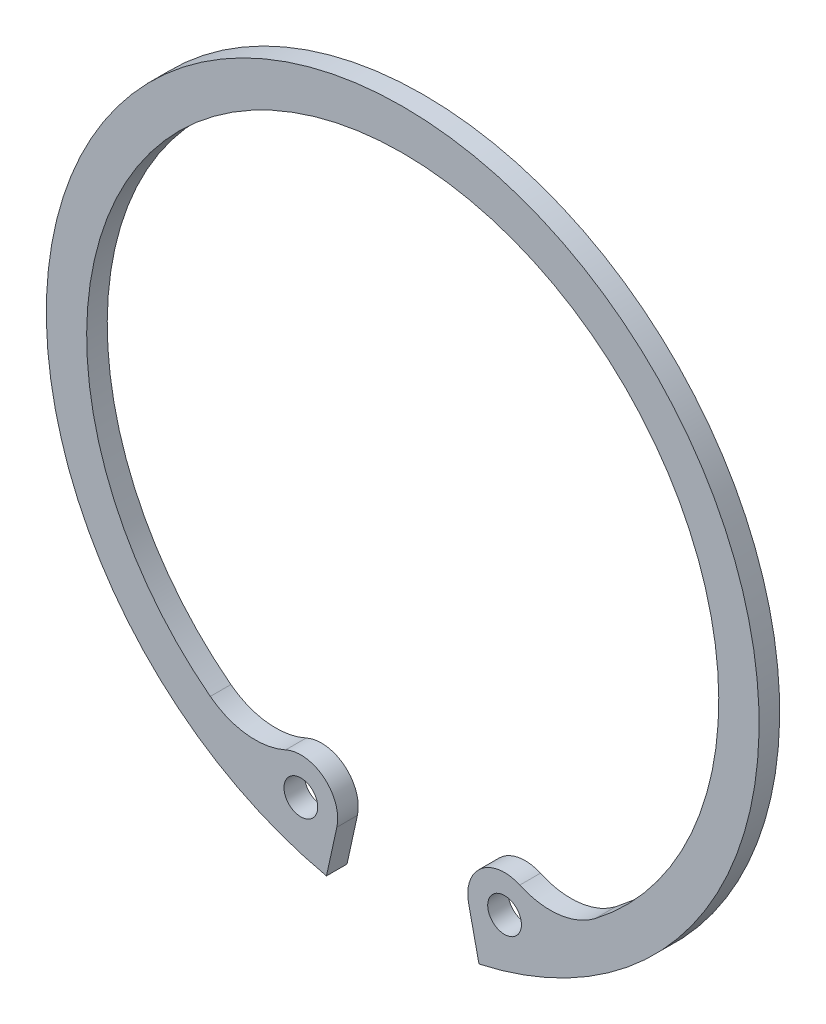
SolidWorks part; units mm, degrees
ref_plane "Plane1" through (0, 0, 0) normal (0, 0, 1) x (1, 0, 0)
ref_plane "Plane2" through (0, 0, 0) normal (0, 1, 0) x (1, 0, 0)
ref_plane "Plane3" through (0, 0, 0) normal (1, 0, 0) x (0, 0, -1)
sketch "Clipboard" plane through (0, 0, 0) normal (0, 0, 1) x (1, 0, 0)
  line L0 (0, 0) -> (1.2446, 0)
  line L1 (0, 0) -> (0, 0.7366)
  line L2 (0, 0) -> (0, -2.5654)
  circle A0 centre (0, 0) radius 0.5207
  circle A1 centre (0, 0) radius 5.5626
  dimension "HoleDia" = 1.0414
  dimension "BoreDia" = 11.1252
  dimension "LargeSection" = 1.2446
  dimension "SmallSection" = 0.7366
  dimension "LugSection" = 2.5654
sketch "BodySke" plane through (0, 0, 0) normal (0, 0, 1) x (1, 0, 0)
  line L0 (-1.5431, 0) -> (1.5431, 0) construction
  line L1 (0, 0) -> (0, 9.7554) construction
  line L2 (2.3536, -10.7453) -> (2.0334, -9.2834)
  line L3 (-2.3536, -10.7453) -> (-2.0334, -9.2834)
  line L4 (0, 0) -> (6.6964, -8.7269) construction
  line L5 (0, 0) -> (-6.6964, -8.7269) construction
  line L6 (-3.0323, -8.5316) -> (-3.2551, -9.5489) construction
  line L7 (1.8537, -3.1509) -> (4.4337, -14.9296) construction
  arc A0 (-2.0334, -9.2834) -> (-3.6141, -8.0055) centre (-3.1437, -9.0402) ccw
  arc A1 (3.6141, -8.0055) -> (2.0334, -9.2834) centre (3.1437, -9.0402) ccw
  arc A2 (5.9387, -7.7395) -> (-5.9387, -7.7395) centre (0, 0) ccw construction
  arc A3 (2.3536, -10.7453) -> (-2.3536, -10.7453) centre (0, 0) ccw
  circle A4 centre (3.1437, -9.0402) radius 0.5207
  circle A5 centre (-3.1437, -9.0402) radius 0.5207
  arc A7 (5.9387, -7.7395) -> (-5.9387, -7.7395) centre (0, 0) ccw
  arc A8 (-3.1437, -9.0402) -> (3.1437, -9.0402) centre (0, 0) ccw construction
  arc A9 (-5.9387, -7.7395) -> (-3.6141, -8.0055) centre (-4.5548, -5.9359) ccw
  arc A10 (3.6141, -8.0055) -> (5.9387, -7.7395) centre (4.5548, -5.9359) ccw
  dimension "D1" = 75
  dimension "GrooveDia" = 22
  dimension "TipRad" = 1.1366
  dimension "HoleOffsetRad" = 9.5712
  dimension "HoleDia" = 1.0414
  dimension "FilletRad" = 2.2733
  dimension "LargeRad" = 9.7554
extrude "Body" add sketch "BodySke" against normal blind 0.635
sketch "ModLugSke" plane through (0, 0, 0) normal (0, 0, 1) x (1, 0, 0)
  line L0 (2.3536, -10.7453) -> (1.9129, -8.7331)
  line L1 (-2.3536, -10.7453) -> (-1.9129, -8.7331)
  line L2 (7.0217, 4.6731) -> (9.1574, 6.0944) construction
  line L3 (-7.0217, 4.6731) -> (-9.1574, 6.0944) construction
  line L4 (-2.3536, -10.7453) -> (-2.0334, -9.2834) construction
  line L5 (2.0334, -9.2834) -> (2.3536, -10.7453) construction
  line L6 (0, 0) -> (0, -12.7358) construction
  line L7 (8.1213, 5.4048) -> (9.1574, 6.0944)
  line L8 (-9.1574, 6.0944) -> (-8.1213, 5.4048)
  arc A0 (2.3536, -10.7453) -> (9.1574, 6.0944) centre (0, 0) ccw
  arc A1 (-7.8216, 3.1569) -> (-2.2807, -8.1204) centre (0, 0) ccw
  arc A2 (2.3536, -10.7453) -> (-2.3536, -10.7453) centre (0, 0) ccw construction
  arc A3 (3.6141, -8.0055) -> (2.0334, -9.2834) centre (3.1437, -9.0402) ccw construction
  arc A4 (-7.8216, 3.1569) -> (-7.9417, 3.7254) centre (-8.3044, 3.3517) ccw
  arc A5 (-8.1213, 5.4048) -> (-7.9417, 3.7254) centre (-7.0217, 4.6731) ccw
  arc A6 (5.9387, -7.7395) -> (-5.9387, -7.7395) centre (0, 0) ccw construction
  arc A7 (7.9417, 3.7254) -> (8.1213, 5.4048) centre (7.0217, 4.6731) ccw
  arc A8 (2.2807, -8.1204) -> (7.8216, 3.1569) centre (0, 0) ccw
  arc A9 (-9.1574, 6.0944) -> (-2.3536, -10.7453) centre (0, 0) ccw
  circle A10 centre (-3.1437, -9.0402) radius 0.5207
  circle A11 centre (-3.1437, -9.0402) radius 0.5207 construction
  circle A12 centre (3.1437, -9.0402) radius 0.5207
  circle A13 centre (3.1437, -9.0402) radius 0.5207 construction
  arc A14 (-2.2807, -8.1204) -> (-1.9129, -8.7331) centre (-2.4215, -8.6217) cw
  arc A15 (2.2807, -8.1204) -> (1.9129, -8.7331) centre (2.4215, -8.6217) ccw
  arc A16 (7.8216, 3.1569) -> (7.9417, 3.7254) centre (8.3044, 3.3517) cw
  point P43 (1.8047, -8.2393)
  dimension "LugAng" = 223.959
extrude "ModLug" [suppressed] add sketch "ModLugSke" against normal through all
equation "' \"BoreDia@Clipboard\" = 8"
equation "' \"Thickness@Body\" = 0.4"
equation "' \"GrooveDia@BodySke\" = 8.4"
equation "' \"LugSection@Clipboard\" = 1.7"
equation "' \"LargeSection@Clipboard\" = 0.85"
equation "' \"SmallSection@Clipboard\" = 0.45"
equation "' \"HoleDia@Clipboard\" = 0.8"
equation "' \"BoreDia@Clipboard\" = 25"
equation "' \"Thickness@Body\" = 1.1"
equation "' \"GrooveDia@BodySke\" = 26.6"
equation "' \"LugSection@Clipboard\" = 4"
equation "' \"LargeSection@Clipboard\" = 2.6"
equation "' \"SmallSection@Clipboard\" = 1.3"
equation "' \"HoleDia@Clipboard\" = 1.5"
